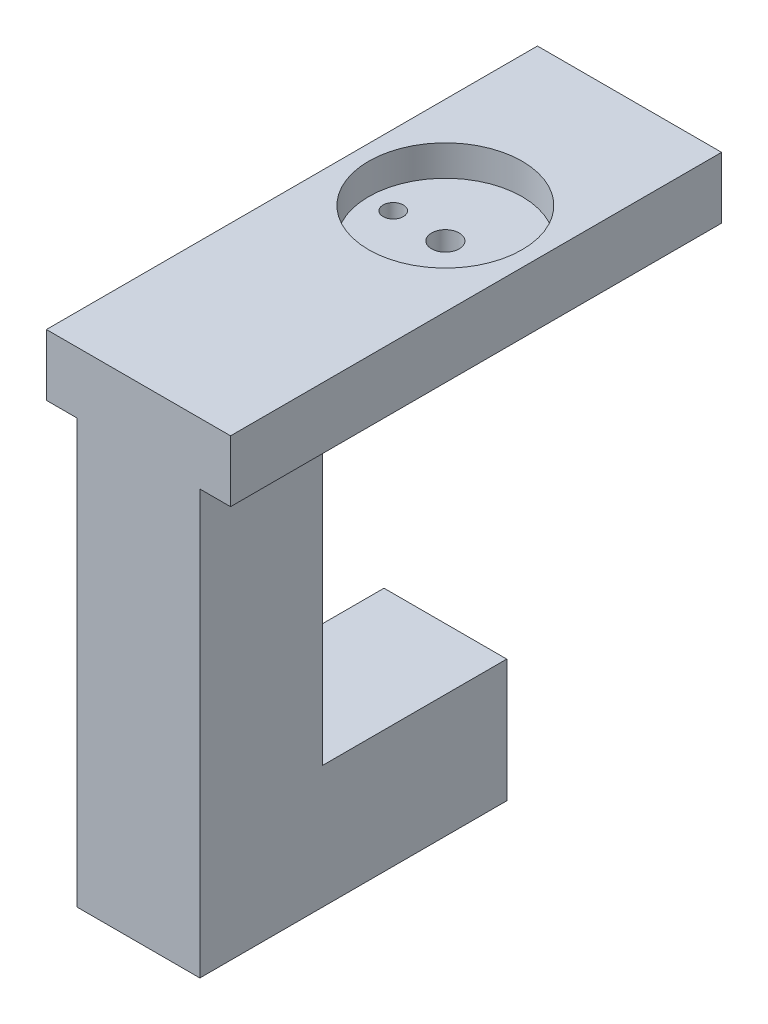
SolidWorks part; units mm, degrees
ref_plane "Alzado" through (0, 0, 0) normal (0, 0, 1) x (1, 0, 0)
ref_plane "Planta" through (0, 0, 0) normal (0, 1, 0) x (1, 0, 0)
ref_plane "Vista lateral" through (0, 0, 0) normal (1, 0, 0) x (0, 0, -1)
sketch "Croquis2" plane through (0, 0, 0) normal (0, 0, 1) x (1, 0, 0)
  line L1 (-10, 10) -> (10, 10)
  line L2 (-10, 10) -> (-10, -10)
  line L3 (-10, -10) -> (10, -10)
  line L4 (10, 10) -> (10, -10)
  line L5 (-10, 10) -> (10, -10) construction
  line L6 (-10, -10) -> (10, 10) construction
  point P0 (0, 0)
  dimension "D1" = 20
  dimension "D2" = 20
extrude "Saliente-Extruir1" add sketch "Croquis2" along normal blind 50
sketch "Croquis3" plane through (0, 10, 0) normal (0, 1, 0) x (1, 0, 0)
  line L0 (10, -50) -> (10, 0) construction
  line L1 (-10, -50) -> (10, -50)
  line L2 (-10, -50) -> (-10, -30)
  line L3 (-10, -30) -> (10, -30)
  line L4 (10, -50) -> (10, -30)
  dimension "D1" = 20
extrude "Saliente-Extruir2" add sketch "Croquis3" along normal blind 59
sketch "Croquis7" plane through (0, 0, 30) normal (0, 0, -1) x (-1, 0, 0)
  line L0 (-15, 69) -> (15, 69)
  line L6 (-10, 69) -> (10, 69) construction
  line L7 (15, 69) -> (15, 59)
  line L9 (0, 69) -> (0, 59) construction
  line L10 (-15, 69) -> (-15, 59)
  line L11 (-15, 59) -> (15, 59)
  dimension "D1" = 15
  dimension "D2" = 10
extrude "Saliente-Extruir4" add sketch "Croquis7" along normal blind 60 and the other way blind 20
sketch "Croquis13" plane through (15, 0, 0) normal (1, 0, 0) x (0, 0, -1)
  line L0 (-50, 59) -> (-30, 59) construction
  line L1 (-30, 59) -> (0, 59) construction
  line L2 (-50, 59) -> (30, 59) construction
  line L3 (0, 59) -> (0, 69) construction
  line L4 (-50, 69) -> (30, 69) construction
sketch "Croquis14" plane through (0, 69, 0) normal (0, 1, 0) x (1, 0, 0)
  line L0 (15, 0) -> (0, 0) construction
  line L1 (15, -30) -> (15, 0) construction
  line L2 (15, -50) -> (15, 30) construction
  circle A0 centre (0, 0) radius 12.5
  circle A1 centre (0, 0) radius 25 construction
  dimension "D1" = 25
  dimension "D2" = 50
extrude "Cortar-Extruir4" cut sketch "Croquis14" against normal blind 5
sketch "Croquis16" plane through (0, 64, 0) normal (0, 1, 0) x (1, 0, 0)
  circle A0 centre (0, 0) radius 2.25
  dimension "D1" = 4.5
extrude "Cortar-Extruir5" cut sketch "Croquis16" against normal blind 10
sketch "Croquis17" plane through (0, 64, 0) normal (0, 1, 0) x (1, 0, 0)
  line L0 (0, 0) -> (0, 8.9888) construction
sketch "Croquis19" plane through (0, 64, 0) normal (0, 1, 0) x (1, 0, 0)
  line L0 (0, 0) -> (8.5, 0) construction
  line L1 (10, 0) -> (-10, 0) construction
  line L2 (0, 0) -> (0, 12.1497) construction
  circle A0 centre (8.5, 0) radius 1.65
  circle A1 centre (-8.5, 0) radius 1.65
  dimension "D2" = 3.3
  dimension "D1" = 8.5
extrude "Cortar-Extruir6" cut sketch "Croquis19" against normal blind 10
